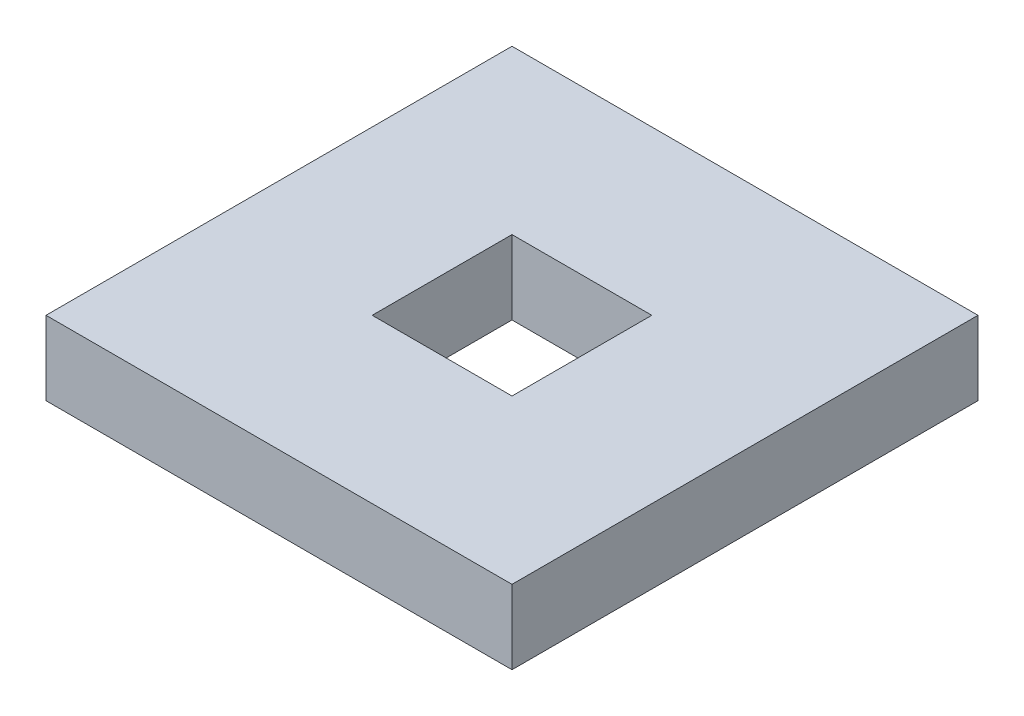
SolidWorks part; units mm, degrees
material "Polyurethane Foam Rigid"
ref_plane "Front Plane" through (0, 0, 0) normal (0, 0, 1) x (1, 0, 0)
ref_plane "Top Plane" through (0, 0, 0) normal (0, 1, 0) x (1, 0, 0)
ref_plane "Right Plane" through (0, 0, 0) normal (1, 0, 0) x (0, 0, -1)
sketch "Sketch1" plane through (0, 0, 0) normal (0, 1, 0) x (1, 0, 0)
  line L1 (20, -20) -> (-20, -20)
  line L2 (20, -20) -> (20, 20)
  line L3 (20, 20) -> (-20, 20)
  line L4 (-20, -20) -> (-20, 20)
  line L5 (20, -20) -> (-20, 20) construction
  line L6 (20, 20) -> (-20, -20) construction
  line L7 (-6, -6) -> (6, -6)
  line L8 (-6, -6) -> (-6, 6)
  line L9 (-6, 6) -> (6, 6)
  line L10 (6, -6) -> (6, 6)
  line L11 (-6, -6) -> (6, 6) construction
  line L12 (-6, 6) -> (6, -6) construction
  point P0 (0, 0)
  point P6 (0, 0)
  dimension "D1" = 40
  dimension "D2" = 40
  dimension "D3" = 12
  dimension "D4" = 12
extrude "Boss-Extrude1" add sketch "Sketch1" along normal blind 6.35
